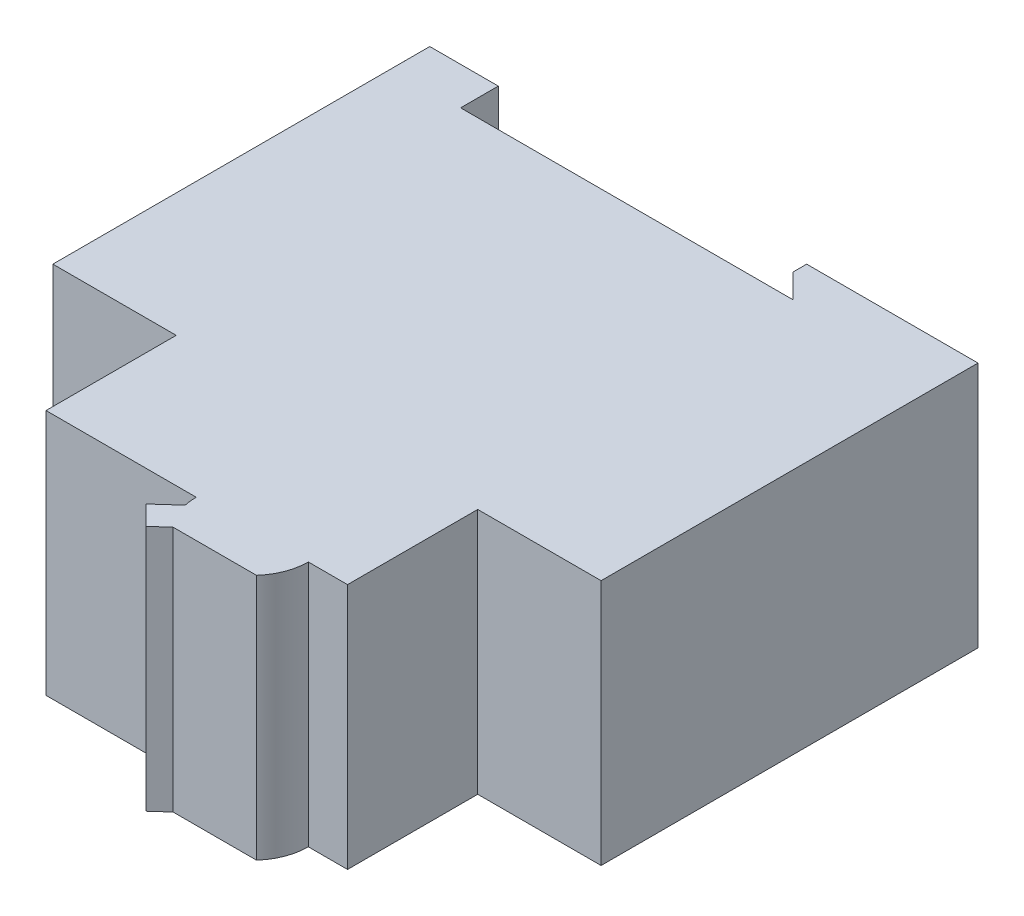
SolidWorks part; units mm, degrees
ref_plane "前视基准面" through (0, 0, 0) normal (0, 0, 1) x (1, 0, 0)
ref_plane "上视基准面" through (0, 0, 0) normal (0, 1, 0) x (1, 0, 0)
ref_plane "右视基准面" through (0, 0, 0) normal (1, 0, 0) x (0, 0, -1)
sketch "草图6" plane through (0, 0, 0) normal (0, 0, 1) x (1, 0, 0)
  line L1 (0, 0) -> (80, 0)
  line L2 (0, 0) -> (0, -31)
  line L3 (0, -31) -> (80, -31)
  line L4 (80, 0) -> (80, -31)
extrude "凸台-拉伸1" add sketch "草图6" along normal blind 85
sketch "草图8" plane through (0, 0, 0) normal (0, 1, 0) x (1, 0, 0)
  line L1 (80, -85) -> (62, -85)
  line L2 (80, -85) -> (80, -55)
  line L3 (80, -55) -> (62, -55)
  line L4 (62, -85) -> (62, -55)
  line L5 (0, -85) -> (18, -85)
  line L6 (0, -85) -> (0, -55)
  line L7 (0, -55) -> (18, -55)
  line L8 (18, -85) -> (18, -55)
extrude "切除-拉伸1" cut sketch "草图8" against normal blind 100
sketch "草图9" plane through (0, 0, 0) normal (0, 1, 0) x (1, 0, 0)
  line L1 (18, -85) -> (62, -85)
  line L2 (18, -85) -> (18, -55)
  line L3 (18, -55) -> (62, -55)
  line L4 (62, -85) -> (62, -55)
  line L5 (0, -55) -> (80, -55)
  line L6 (0, -55) -> (0, 0)
  line L7 (0, 0) -> (80, 0)
  line L8 (80, -55) -> (80, 0)
  line M1 (0, 0) -> (0, -55)
  line M2 (0, -55) -> (18, -55)
  line M3 (18, -55) -> (18, -85)
  line M4 (18, -85) -> (62, -85)
  line M5 (62, -85) -> (62, -55)
  line M6 (62, -55) -> (80, -55)
  line M7 (80, -55) -> (80, 0)
  line M8 (80, 0) -> (0, 0)
extrude "凸台-拉伸3" add sketch "草图9" along normal blind 5 contours L3 M2 M6 M7 M8 M1 | L3 M3 M4 M5
sketch "草图10" plane through (0, -31, 0) normal (0, -1, 0) x (1, 0, 0)
  line L0 (0, 0) -> (10, 0)
  line L1 (80, 0) -> (0, 0) construction
  line L2 (80, 0) -> (55, 0)
  line L3 (55, 0) -> (55, 2)
  line L4 (10, 0) -> (55, 0)
  line L5 (10, 0) -> (10, 5.5)
  line L6 (10, 5.5) -> (58.5, 5.5)
  line L7 (55, 2) -> (58.5, 5.5)
  line L8 (10, 0) -> (55, 0)
  line L9 (42.0163, 79.469) -> (39.9194, 81.3542)
  line L10 (62, 85) -> (62, 55) construction
  line L11 (62, 74) -> (56.2798, 74)
  line L12 (18, 55) -> (18, 85) construction
  line L14 (37.091, 78.5257) -> (39.9194, 81.3542)
  line L15 (42.0163, 79.469) -> (54.1829, 79.469)
  line L16 (40.1204, 75.8022) -> (37.091, 78.5257)
  line L17 (39.9194, 74) -> (18, 74)
  line L18 (18, 74) -> (18, 85)
  line L19 (18, 85) -> (62, 85)
  line L20 (18, 85) -> (62, 85) construction
  line L21 (62, 85) -> (62, 74)
  arc A0 (40.1204, 75.8022) -> (39.9194, 74) centre (48.0996, 74) ccw
  arc A1 (56.2798, 74) -> (54.1829, 79.469) centre (48.0996, 74) ccw
  line M24 (18, 85) -> (18, 55)
  line M27 (0, 0) -> (80, 0)
  line M30 (62, 55) -> (62, 85)
  line M31 (62, 85) -> (18, 85)
extrude "切除-拉伸2" cut sketch "草图10" against normal blind 110 contours L3 L7 L6 L5 M27 | A1 L11 L17 A0 L16 L14 L9 L15 M30 M31 M24
